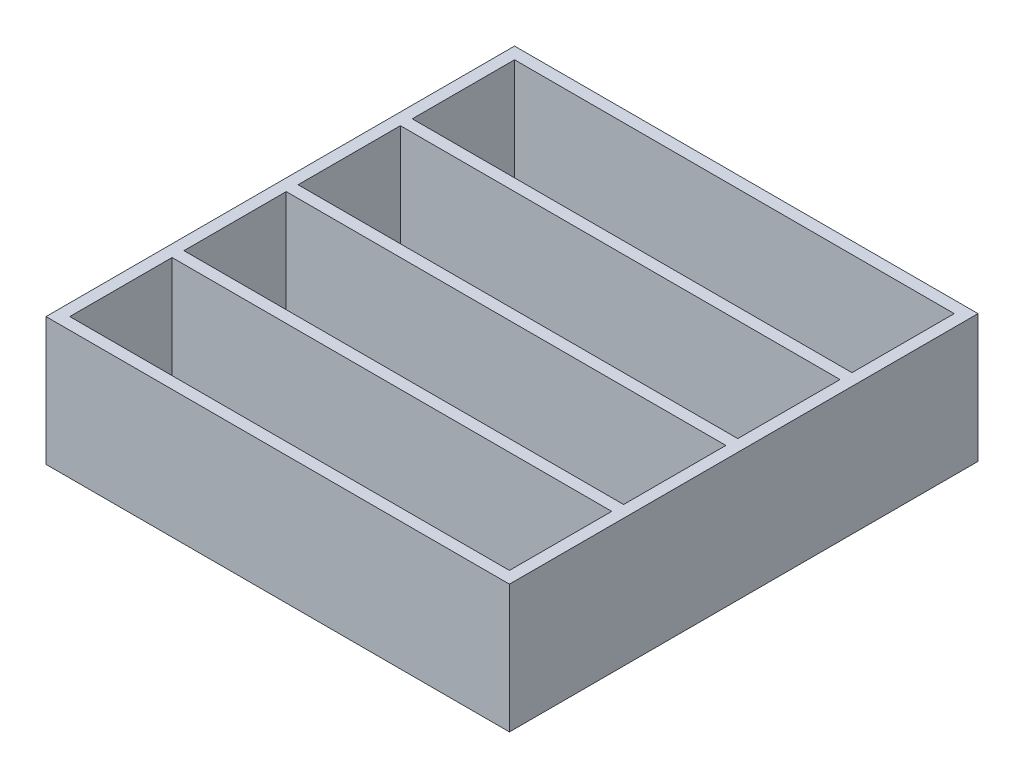
SolidWorks part; units mm, degrees
ref_plane "Front Plane" through (0, 0, 0) normal (0, 0, 1) x (1, 0, 0)
ref_plane "Top Plane" through (0, 0, 0) normal (0, 1, 0) x (1, 0, 0)
ref_plane "Right Plane" through (0, 0, 0) normal (1, 0, 0) x (0, 0, -1)
sketch "Sketch1" plane through (0, 0, 0) normal (0, 1, 0) x (1, 0, 0)
  line L1 (-65.4717, -18.3834) -> (12.5083, -18.3834)
  line L2 (-65.4717, -18.3834) -> (-65.4717, 60.4566)
  line L3 (-65.4717, 60.4566) -> (12.5083, 60.4566)
  line L4 (12.5083, -18.3834) -> (12.5083, 60.4566)
  dimension "D1" = 78.84
  dimension "D2" = 77.98
extrude "Boss-Extrude1" add sketch "Sketch1" along normal blind 21.54
sketch "Sketch4" plane through (0, 21.54, 0) normal (0, 1, 0) x (1, 0, 0)
  line L0 (-65.4717, 60.4566) -> (-65.4717, -18.3834) construction
  line L1 (10.5083, -16.3834) -> (-63.4717, -16.3834)
  line L2 (10.5083, -16.3834) -> (10.5083, 0.8266)
  line L3 (10.5083, 0.8266) -> (-63.4717, 0.8266)
  line L4 (-63.4717, -16.3834) -> (-63.4717, 0.8266)
  line L5 (-65.4717, -18.3834) -> (12.5083, -18.3834) construction
  line L6 (10.5083, 2.8266) -> (-63.4717, 2.8266)
  line L7 (10.5083, 2.8266) -> (10.5083, 20.0366)
  line L8 (10.5083, 20.0366) -> (-63.4717, 20.0366)
  line L9 (-63.4717, 2.8266) -> (-63.4717, 20.0366)
  line L10 (10.5083, 22.0366) -> (-63.4717, 22.0366)
  line L11 (10.5083, 22.0366) -> (10.5083, 39.2466)
  line L12 (10.5083, 39.2466) -> (-63.4717, 39.2466)
  line L13 (-63.4717, 22.0366) -> (-63.4717, 39.2466)
  line L14 (10.5083, 41.2466) -> (-63.4717, 41.2466)
  line L15 (10.5083, 41.2466) -> (10.5083, 58.4566)
  line L16 (10.5083, 58.4566) -> (-63.4717, 58.4566)
  line L17 (-63.4717, 41.2466) -> (-63.4717, 58.4566)
  dimension "D1" = 73.98
  dimension "D2" = 17.21
  dimension "D3" = 2
  dimension "D4" = 2
  dimension "D5" = 73.98
  dimension "D6" = 17.21
  dimension "D7" = 17.21
  dimension "D8" = 17.21
  dimension "D9" = 73.98
  dimension "D10" = 73.98
  dimension "D11" = 2
  dimension "D12" = 2
  dimension "D13" = 2
  dimension "D14" = 2
  dimension "D15" = 2
  dimension "D16" = 2
extrude "Cut-Extrude2" cut sketch "Sketch4" against normal blind 19.54
